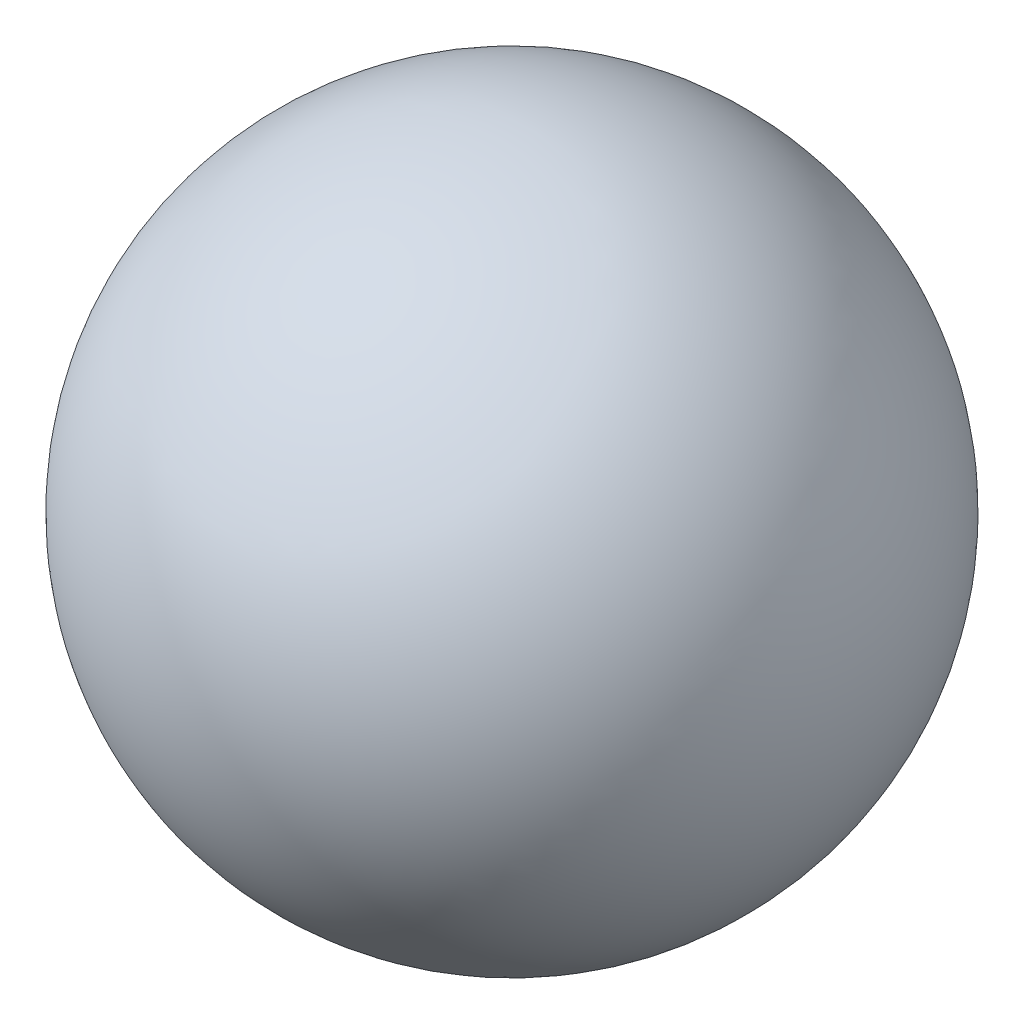
SolidWorks part; units mm, degrees
ref_plane "Front Plane" through (0, 0, 0) normal (0, 0, 1) x (1, 0, 0)
ref_plane "Top Plane" through (0, 0, 0) normal (0, 1, 0) x (1, 0, 0)
ref_plane "Right Plane" through (0, 0, 0) normal (1, 0, 0) x (0, 0, -1)
sketch "Sketch2" plane through (0, 0, 0) normal (0, 1, 0) x (1, 0, 0)
  line L0 (0, 19.939) -> (0, -19.939)
  arc A0 (0, 19.939) -> (0, -19.939) centre (0, 0) ccw
revolve "Revolve1" add sketch "Sketch2" angle 360 about L0
